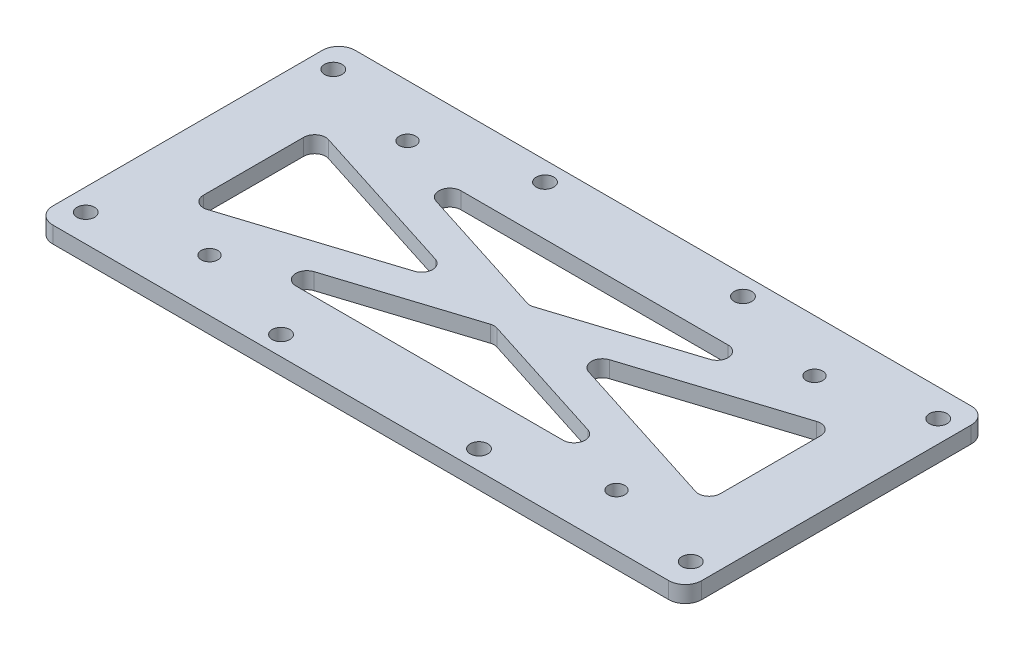
SolidWorks part; units mm, degrees
material "Thornel Mat VMA"
ref_plane "前视基准面" through (0, 0, 0) normal (0, 0, 1) x (1, 0, 0)
ref_plane "上视基准面" through (0, 0, 0) normal (0, 1, 0) x (1, 0, 0)
ref_plane "右视基准面" through (0, 0, 0) normal (1, 0, 0) x (0, 0, -1)
other "Configuration Table"
sketch "草图1" plane through (0, 0, 0) normal (0, 1, 0) x (1, 0, 0)
  line L1 (55, -22.5) -> (-55, -22.5) construction
  line L2 (55, -22.5) -> (55, 22.5) construction
  line L3 (55, 22.5) -> (-55, 22.5) construction
  line L4 (-55, -22.5) -> (-55, 22.5) construction
  line L5 (55, -22.5) -> (-55, 22.5) construction
  line L6 (55, 22.5) -> (-55, -22.5) construction
  line L7 (59, -27.5) -> (-59, -27.5)
  line L8 (59, -27.5) -> (59, 27.5)
  line L9 (59, 27.5) -> (-59, 27.5)
  line L10 (-59, -27.5) -> (-59, 27.5)
  line L11 (59, -27.5) -> (-59, 27.5) construction
  line L12 (59, 27.5) -> (-59, -27.5) construction
  line L13 (18, -24) -> (-18, -24) construction
  line L14 (18, -24) -> (18, 24) construction
  line L15 (18, 24) -> (-18, 24) construction
  line L16 (-18, -24) -> (-18, 24) construction
  line L17 (18, -24) -> (-18, 24) construction
  line L18 (18, 24) -> (-18, -24) construction
  circle A0 centre (-55, 22.5) radius 1.6
  circle A1 centre (55, 22.5) radius 1.6
  circle A2 centre (-55, -22.5) radius 1.6
  circle A3 centre (55, -22.5) radius 1.6
  circle A4 centre (-18, 24) radius 1.6
  circle A5 centre (18, 24) radius 1.6
  circle A6 centre (18, -24) radius 1.6
  circle A7 centre (-18, -24) radius 1.6
  point P0 (0, 0)
  point P10 (0, 0)
  point P15 (0, 0)
  dimension "D3" = 3.2
  dimension "D8" = 3.2
  dimension "D1" = 110
  dimension "D2" = 45
  dimension "D4" = 5
  dimension "D5" = 4
  dimension "D6" = 36
  dimension "D7" = 48
extrude "凸台-拉伸1" add sketch "草图1" along normal blind 3
sketch "草图2" plane through (0, 3, 0) normal (0, 1, 0) x (1, 0, 0)
  line L1 (37, -18) -> (-37, -18) construction
  line L2 (37, -18) -> (37, 18) construction
  line L3 (37, 18) -> (-37, 18) construction
  line L4 (-37, -18) -> (-37, 18) construction
  line L5 (37, -18) -> (-37, 18) construction
  line L6 (37, 18) -> (-37, -18) construction
  circle A0 centre (-37, 18) radius 1.5
  circle A1 centre (37, 18) radius 1.5
  circle A2 centre (37, -18) radius 1.5
  circle A3 centre (-37, -18) radius 1.5
  point P0 (0, 0)
  dimension "D3" = 3
  dimension "D1" = 74
  dimension "D2" = 36
extrude "切除-拉伸1" cut sketch "草图2" against normal through all
sketch "草图3" plane through (0, 3, 0) normal (0, 1, 0) x (1, 0, 0)
  line L0 (-59, 27.5) -> (-59, -27.5) construction
  line L1 (47, -15) -> (-47, -15)
  line L2 (47, -15) -> (47, 15)
  line L3 (47, 15) -> (-47, 15)
  line L4 (-47, -15) -> (-47, 15)
  line L5 (47, -15) -> (-47, 15) construction
  line L6 (47, 15) -> (-47, -15) construction
  line L7 (47.9121, -12.142) -> (-46.0879, 17.858)
  line L8 (46.0879, 17.858) -> (-47.9121, -12.142)
  line L9 (46.0879, -17.858) -> (-47.9121, 12.142)
  line L10 (47.9121, 12.142) -> (-46.0879, -17.858)
  circle A0 centre (-37, 18) radius 1.5 construction
  point P0 (0, 0)
  dimension "D1" = 12
  dimension "D2" = 3
  dimension "D3" = 3
  dimension "D4" = 3
extrude "切除-拉伸2" cut sketch "草图3" against normal through all contours L8 L9 L4 | L8 L3 L7 | L2 L10 L7 | L9 L10 L1
fillet "圆角1" radius 2 12 edges at (-47, 1.5, -11.8509) (-9.8671, 1.5, 0) (-47, 1.5, 11.8509) (-37.1329, 1.5, 15) (0, 1.5, 3.1491) (37.1329, 1.5, 15) (47, 1.5, 11.8509) (47, 1.5, -11.8509) (9.8671, 1.5, 0) (37.1329, 1.5, -15) (0, 1.5, -3.1491) (-37.1329, 1.5, -15)
fillet "圆角2" radius 3 4 edges at (59, 1.5, -27.5) (59, 1.5, 27.5) (-59, 1.5, 27.5) (-59, 1.5, -27.5)
